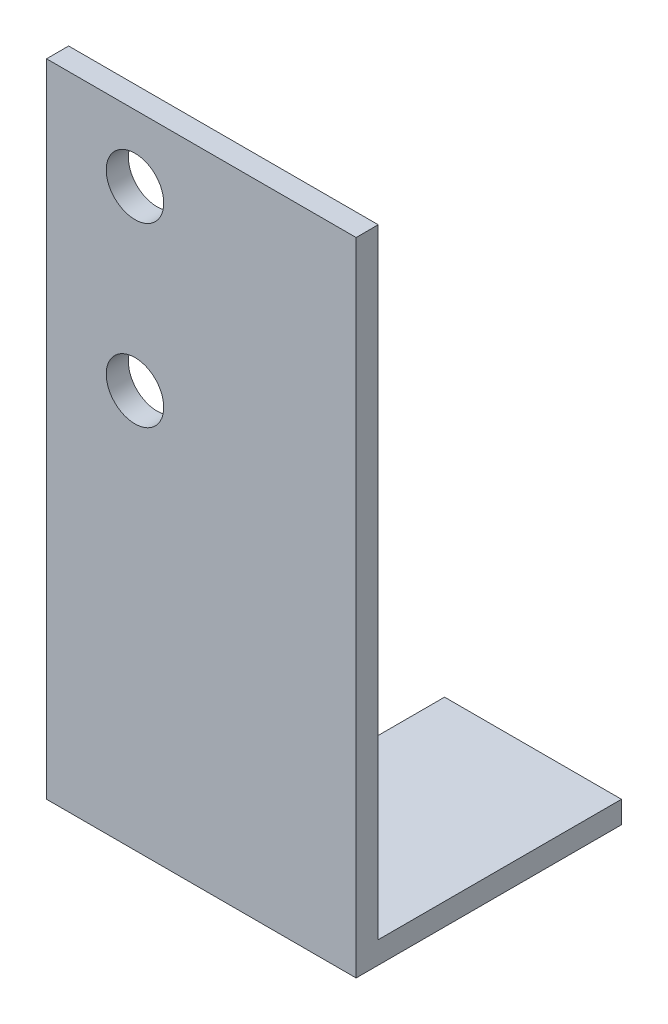
SolidWorks part; units mm, degrees
ref_plane "前基準面" through (0, 0, 0) normal (0, 0, 1) x (1, 0, 0)
ref_plane "上基準面" through (0, 0, 0) normal (0, 1, 0) x (1, 0, 0)
ref_plane "右基準面" through (0, 0, 0) normal (1, 0, 0) x (0, 0, -1)
sketch "草圖1" plane through (0, 0, 0) normal (1, 0, 0) x (0, 0, -1)
  line L0 (0, 0) -> (12, 0)
  line L1 (12, 0) -> (12, 1)
  line L2 (12, 1) -> (1, 1)
  line L3 (1, 1) -> (1, 29)
  line L4 (1, 29) -> (0, 29)
  line L5 (0, 29) -> (0, 0)
  dimension "D1" = 1
  dimension "D2" = 1
  dimension "D3" = 29
  dimension "D4" = 12
extrude "填料-伸長1" add sketch "草圖1" along normal blind 14
sketch "草圖2" plane through (0, 0, 0) normal (0, 0, 1) x (1, 0, 0)
  line L0 (0, 1) -> (0, 29) construction
  line L2 (14, 29) -> (0, 29) construction
  circle A0 centre (4, 26) radius 1.3
  circle A1 centre (4, 18) radius 1.3
  dimension "D1" = 2.6
  dimension "D2" = 3
  dimension "D3" = 8
  dimension "D4" = 4
extrude "除料-伸長1" cut sketch "草圖2" against normal through all
sketch "草圖4" plane through (0, 1, 0) normal (0, 1, 0) x (1, 0, 0)
  line L0 (14, 1) -> (0, 1) construction
  line L1 (0, 12) -> (6, 12)
  line L2 (0, 12) -> (0, 1)
  line L3 (0, 1) -> (6, 1)
  line L4 (6, 12) -> (6, 1)
  line L5 (14, 12) -> (14, 1) construction
  dimension "D1" = 8
extrude "除料-伸長3" cut sketch "草圖4" against normal through all
